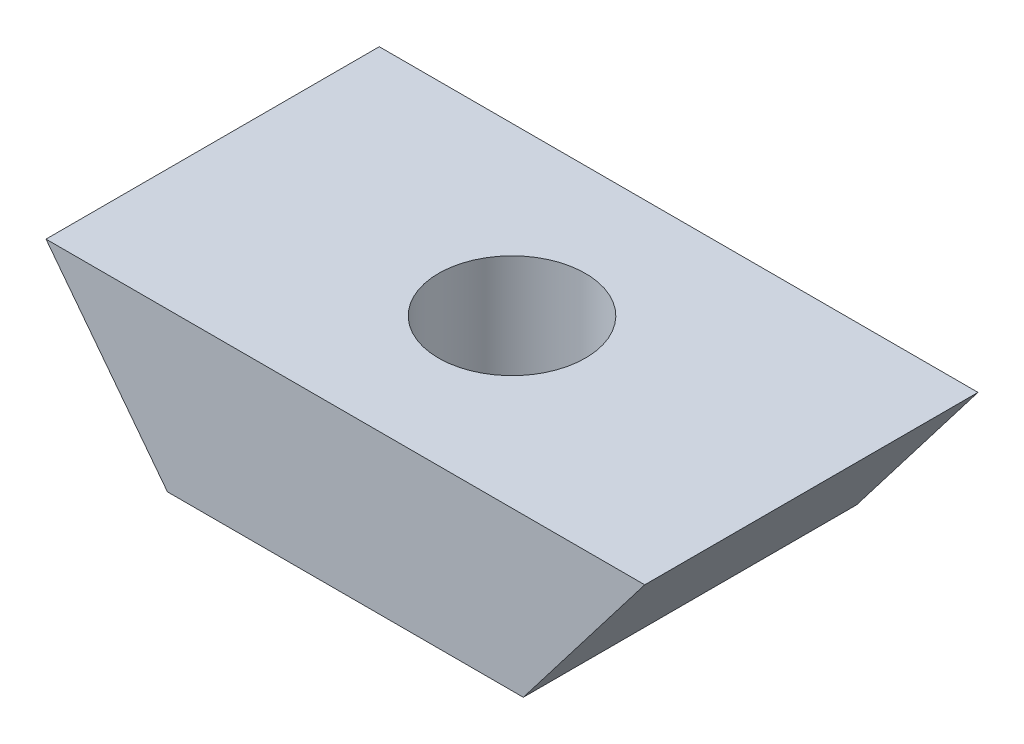
SolidWorks part; units mm, degrees
ref_plane "前视基准面" through (0, 0, 0) normal (0, 0, 1) x (1, 0, 0)
ref_plane "上视基准面" through (0, 0, 0) normal (0, 1, 0) x (1, 0, 0)
ref_plane "右视基准面" through (0, 0, 0) normal (1, 0, 0) x (0, 0, -1)
other "Configuration Table"
sketch "草图1" plane through (0, 0, 0) normal (0, 0, 1) x (1, 0, 0)
  line L0 (0, 0) -> (10.6, 0)
  line L1 (0.7119, -2.8) -> (10.6, -2.8) construction
  line L2 (10.6, 0) -> (8.45, -2.8)
  line L3 (8.45, -2.8) -> (2.15, -2.8)
  line L4 (2.15, -2.8) -> (0, 0)
  point P5 (5.3, 0)
  point P8 (5.3, -2.8)
  point P9 (0, 0)
  point P10 (8.8544, -2.8)
  dimension "D1" = 10.6
  dimension "D2" = 2.8
  dimension "D3" = 6.3
extrude "凸台-拉伸1" add sketch "草图1" along normal blind 5.9
sketch "草图2" plane through (0, 0, 0) normal (0, 1, 0) x (1, 0, 0)
  circle A0 centre (5.3, -2.95) radius 1.3
  dimension "D1" = 2.6
extrude "切除-拉伸1" cut sketch "草图2" against normal blind 5.9
